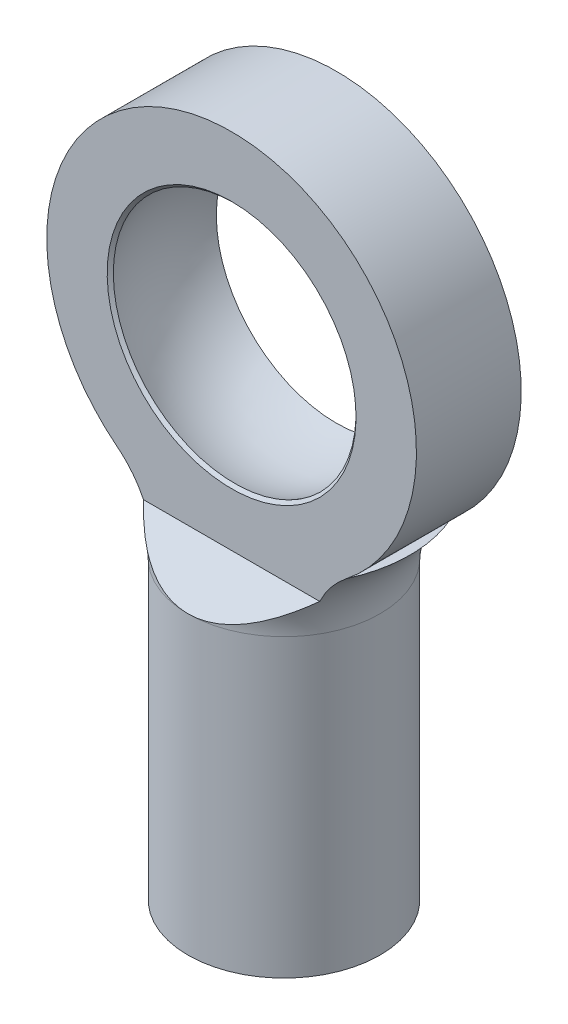
SolidWorks part; units mm, degrees
ref_plane "Front Plane" through (0, 0, 0) normal (0, 0, 1) x (1, 0, 0)
ref_plane "Top Plane" through (0, 0, 0) normal (0, 1, 0) x (1, 0, 0)
ref_plane "Right Plane" through (0, 0, 0) normal (1, 0, 0) x (0, 0, -1)
sketch "Sketch1" plane through (0, 0, 0) normal (0, 0, 1) x (1, 0, 0)
  line L0 (0, 0) -> (0, -6.5043) construction
  line L2 (0, 11) -> (0, 0)
  line L3 (0, 0) -> (2.75, 0)
  line L4 (2.75, 8.4637) -> (2.75, 0)
  line L5 (0, 20) -> (0, 11)
  arc A0 (3.6094, 10.35) -> (0, 20) centre (0, 14.5) ccw
  arc A1 (3.6094, 10.35) -> (2.75, 8.4637) centre (5.25, 8.4637) ccw
  dimension "D1" = 11
  dimension "D3" = 2.5
  dimension "D2" = 14.5
  dimension "D4" = 2.75
revolve "Revolve1" add sketch "Sketch1" angle 360 about L0
sketch "Sketch2" plane through (0, 0, 0) normal (1, 0, 0) x (0, 0, -1)
  line L0 (-6.5, 9.4068) -> (-2.75, 8.4637)
  line L1 (-6.5, 20.4068) -> (-1.5, 20.4068)
  line L2 (-6.5, 20.4068) -> (-6.5, 9.4068)
  line L4 (-1.5, 20.4068) -> (-1.5, 9.4068)
  line L5 (-2.75, 8.4637) -> (-1.5, 9.4068)
  line L10 (6.5, 20.4068) -> (6.5, 9.4068)
  line L11 (6.5, 20.4068) -> (1.5, 20.4068)
  line L12 (1.5, 20.4068) -> (1.5, 9.4068)
  line L13 (-3.6094, 10.35) -> (3.6094, 10.35) construction
  line L14 (-2.75, 8.4637) -> (2.75, 8.4637) construction
  line L15 (-3.6094, 10.35) -> (3.6094, 10.35) construction
  line L16 (-2.75, 8.4637) -> (2.75, 8.4637) construction
  line L17 (0, 10.35) -> (0, 8.4637) construction
  line L18 (2.75, 8.4637) -> (1.5, 9.4068)
  line L19 (6.5, 9.4068) -> (2.75, 8.4637)
  point P4 (0, 9.4068)
  dimension "D1" = 5
  dimension "D2" = 1.5
  dimension "D3" = 11
extrude "Cut-Extrude1" cut sketch "Sketch2" against normal through all both and the other way through all
sketch "Sketch3" plane through (0, 0, 0) normal (0, 0, 1) x (1, 0, 0)
  arc A1 (3.2829, 10.35) -> (-3.2829, 10.35) centre (0, 14.5) ccw construction
  arc A2 (3.2829, 10.35) -> (-3.2829, 10.35) centre (0, 14.5) ccw construction
  circle A3 centre (0, 14.5) radius 3
  dimension "D1" = 6
extrude "Cut-Extrude2" cut sketch "Sketch3" against normal through all both and the other way through all
sketch "Sketch5" plane through (0, 0, 0) normal (0, 0, 1) x (1, 0, 0)
  line L0 (0, 18.25) -> (0, 10.75)
  arc A1 (0, 10.75) -> (0, 18.25) centre (0, 14.5) ccw
  circle A2 centre (0, 14.5) radius 3 construction
  dimension "D1" = 7.5
revolve "Cut-Revolve2" cut sketch "Sketch5" angle 360 about L0
chamfer "Chamfer1" distance 0.125 angle 45 1 edges at (0, 17.9369, 1.5)
sketch "Sketch6" plane through (0, 0, 1.5) normal (0, 0, 1) x (1, 0, 0)
  line L2 (-3.6094, 10.35) -> (-3.2829, 10.35)
  line L3 (3.2829, 10.35) -> (3.6094, 10.35)
  arc A3 (3.6094, 10.35) -> (-3.6094, 10.35) centre (0, 14.5) ccw construction
  arc A4 (3.6094, 10.35) -> (-3.6094, 10.35) centre (0, 14.5) ccw
  arc A5 (3.2829, 10.35) -> (-3.2829, 10.35) centre (0, 14.5) ccw construction
  arc A6 (3.2829, 10.35) -> (-3.2829, 10.35) centre (0, 14.5) ccw
extrude "Cut-Extrude3" cut sketch "Sketch6" against normal through all both
sketch "Sketch7" plane through (0, 0, 0) normal (0, -1, 0) x (1, 0, 0)
  circle A0 centre (0, 0) radius 1.5
  dimension "D1" = 3
extrude "Cut-Extrude4" cut sketch "Sketch7" against normal blind 5
ref_point "Point1"
